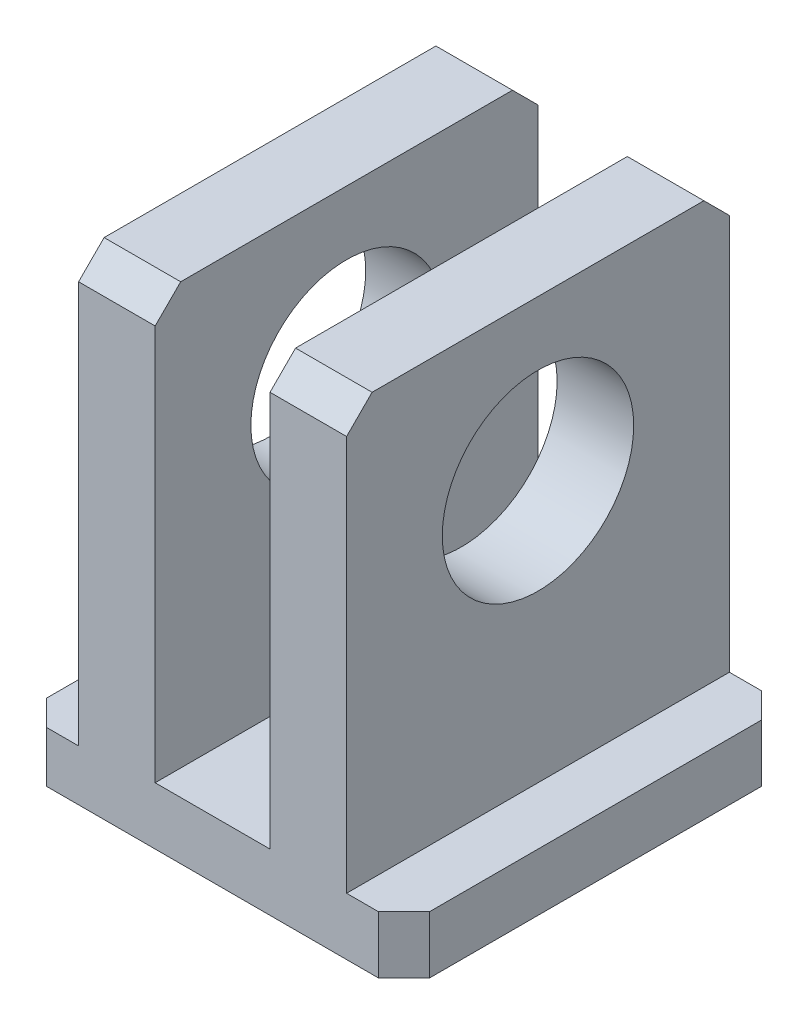
SolidWorks part; units mm, degrees
ref_plane "前视基准面" through (0, 0, 0) normal (0, 0, 1) x (1, 0, 0)
ref_plane "上视基准面" through (0, 0, 0) normal (0, 1, 0) x (1, 0, 0)
ref_plane "右视基准面" through (0, 0, 0) normal (1, 0, 0) x (0, 0, -1)
other "Configuration Table"
sketch "草图1" plane through (0, 0, 0) normal (0, 1, 0) x (1, 0, 0)
  line L0 (13, -15) -> (15, -13)
  line L1 (-13, 15) -> (13, 15)
  line L2 (-15, 13) -> (-15, -13)
  line L3 (-13, -15) -> (13, -15)
  line L4 (15, 13) -> (15, -13)
  line L5 (-15, 15) -> (15, -15) construction
  line L6 (-15, -15) -> (15, 15) construction
  line L7 (-15, -13) -> (-13, -15)
  line L8 (-15, 13) -> (-13, 15)
  line L9 (13, 15) -> (15, 13)
  point P0 (0, 0)
  dimension "D1" = 30
  dimension "D2" = 30
extrude "凸台-拉伸1" add sketch "草图1" along normal blind 37.5 contours L1 L9 L4 L0 L3 L7 L2 L8
sketch "草图4" plane through (0, 37.5, 0) normal (0, 1, 0) x (1, 0, 0)
  line L0 (-13, -15) -> (-13, 15)
  line L1 (-13, -15) -> (-10.5, -15)
  line L2 (-13, 15) -> (-10.5, 15)
  line L3 (-10.5, -15) -> (-10.5, 15)
  dimension "D1" = 2.5
sketch "草图5" plane through (0, 37.5, 0) normal (0, 1, 0) x (1, 0, 0)
  line L0 (0, -15) -> (0, 15)
  line L1 (-13, -15) -> (13, -15) construction
  line L2 (-13, 15) -> (13, 15) construction
extrude "切除-拉伸2" cut sketch "草图4" against normal blind 33.5 contours L2 L3 L1 L0
sketch "草图9" plane through (0, 37.5, 0) normal (0, 1, 0) x (1, 0, 0)
  line L0 (-13, 15) -> (-15, 13)
  line L1 (-15, 13) -> (-15, -13)
  line L2 (-15, -13) -> (-13, -15)
extrude "切除-拉伸3" cut sketch "草图9" against normal blind 33.5 and the other way through all
sketch "草图11" plane through (0, 37.5, 0) normal (0, 1, 0) x (1, 0, 0)
  line L1 (0, -15) -> (0, 15)
  line L2 (10.5, -15) -> (10.5, 15)
  line L3 (13, -15) -> (10.5, -15)
  line L4 (15, -13) -> (13, -15)
  line L5 (15, 13) -> (15, -13)
  line L6 (-10.5, 15) -> (-13, 15)
  line L7 (-13, 15) -> (-15, 13)
  line L8 (-15, 13) -> (-15, -13)
  line L9 (-15, -13) -> (-13, -15)
  line L10 (-13, -15) -> (-10.5, -15)
  line L11 (-10.5, -15) -> (-10.5, 15)
  line L12 (-10.5, 15) -> (-13, 15)
  line L13 (-13, 15) -> (-15, 13)
  line L14 (-15, 13) -> (-15, -13)
  line L15 (-15, -13) -> (-13, -15)
  line L16 (-13, -15) -> (-10.5, -15)
  line L17 (-10.5, -15) -> (-10.5, 15)
  line L18 (13, 15) -> (15, 13)
  line L19 (10.5, 15) -> (13, 15)
  dimension "D1" = 0
extrude "切除-拉伸4" cut sketch "草图11" against normal blind 33 contours L18 L5 L4 L3 L2 L19
sketch "草图12" plane through (0, 37.5, 0) normal (0, 1, 0) x (1, 0, 0)
  line L0 (-10.5, 15) -> (10.5, 15) construction
  line L1 (4.5, -15) -> (-4.5, -15)
  line L2 (0, -15) -> (0, 15)
  line L3 (4.5, 15) -> (-4.5, 15)
  line L4 (-4.5, -15) -> (-4.5, 15)
  line L5 (4.5, -15) -> (4.5, 15)
  dimension "D1" = 4.5
extrude "切除-拉伸7" cut sketch "草图12" against normal blind 33 contours L5 L3 L4 L1
sketch "草图16" plane through (-10.5, 0, 0) normal (-1, 0, 0) x (0, 0, 1)
  line L0 (0, 0) -> (0, 37.5)
  line L1 (15, 37.5) -> (-15, 37.5) construction
  circle A0 centre (0, 25) radius 7.5
  dimension "D1" = 25
extrude "切除-拉伸8" cut sketch "草图16" against normal up to surface (21 mm away) contours A0 up to face at (10.5, 21, 0)
chamfer "倒角2" distance 2 angle 45 4 edges at (7.5, 37.5, 15) (7.5, 37.5, -15) (-7.5, 37.5, 15) (-7.5, 37.5, -15)
